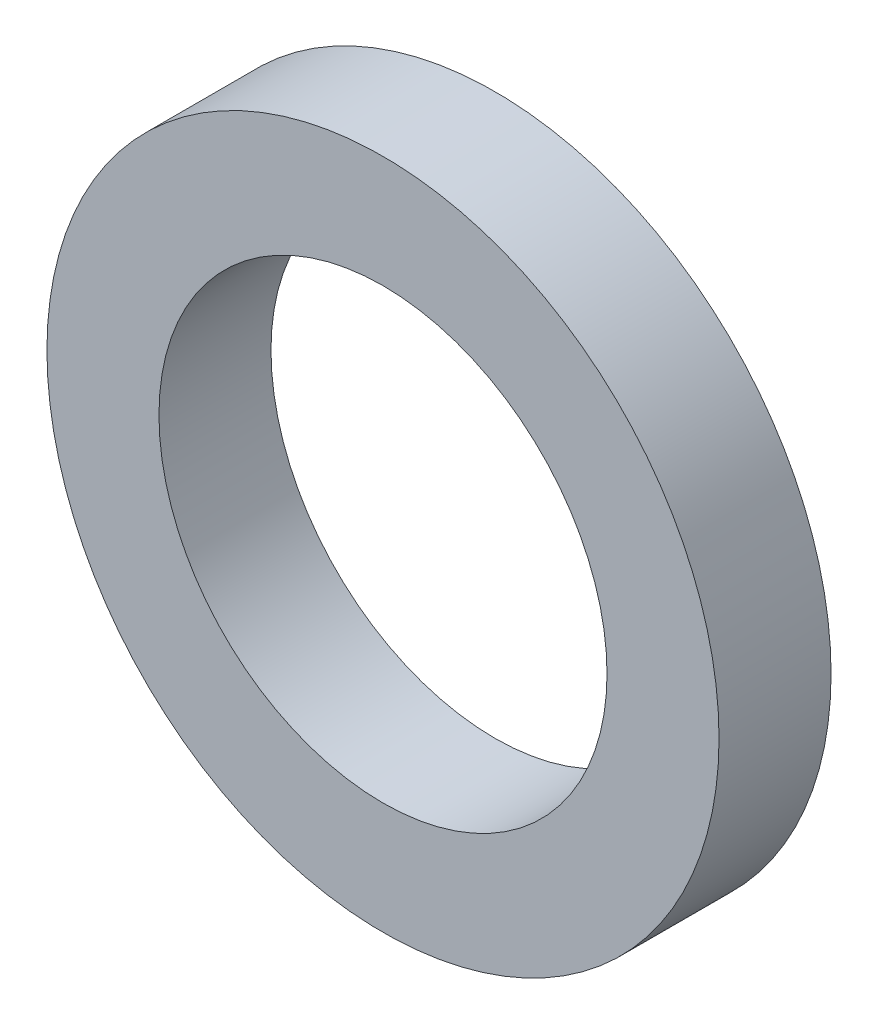
SolidWorks part; units mm, degrees
ref_plane "前视基准面" through (0, 0, 0) normal (0, 0, 1) x (1, 0, 0)
ref_plane "上视基准面" through (0, 0, 0) normal (0, 1, 0) x (1, 0, 0)
ref_plane "右视基准面" through (0, 0, 0) normal (1, 0, 0) x (0, 0, -1)
sketch "草图1" plane through (0, 0, 0) normal (0, 0, 1) x (1, 0, 0)
  circle A0 centre (0, 0) radius 2
  dimension "D1" = 4
extrude "拉伸-薄壁1" add sketch "草图1" along normal blind 1 thin
